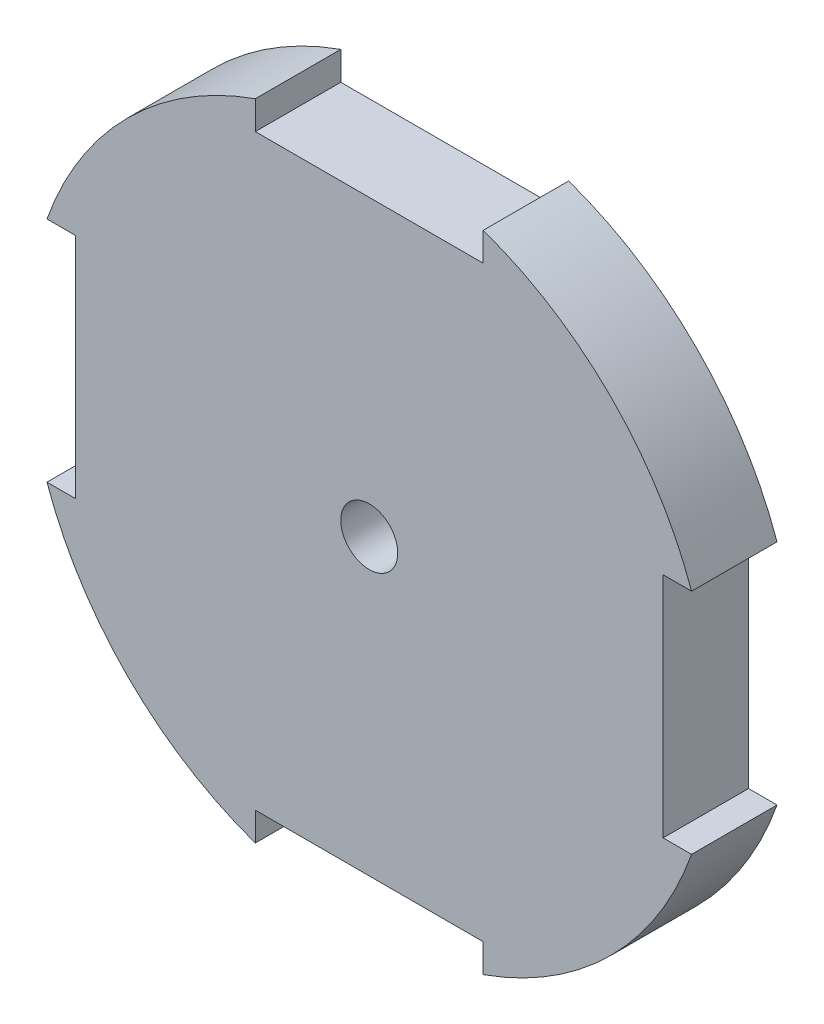
SolidWorks part; units mm, degrees
material "6061 Alloy"
ref_plane "Front Plane" through (0, 0, 0) normal (0, 0, 1) x (1, 0, 0)
ref_plane "Top Plane" through (0, 0, 0) normal (0, 1, 0) x (1, 0, 0)
ref_plane "Right Plane" through (0, 0, 0) normal (1, 0, 0) x (0, 0, -1)
sketch "Sketch1" plane through (0, 0, 0) normal (0, 0, 1) x (1, 0, 0)
  line L0 (-25.4, 71.842) -> (-25.4, 65.492)
  line L1 (-25.4, 65.492) -> (25.4, 65.492)
  line L2 (25.4, 65.492) -> (25.4, 71.842)
  line L3 (65.492, 25.4) -> (65.492, -25.4)
  line L4 (71.842, 25.4) -> (65.492, 25.4)
  line L5 (65.492, -25.4) -> (71.842, -25.4)
  line L6 (25.4, -65.492) -> (-25.4, -65.492)
  line L7 (25.4, -71.842) -> (25.4, -65.492)
  line L8 (-25.4, -65.492) -> (-25.4, -71.842)
  line L9 (-65.492, -25.4) -> (-65.492, 25.4)
  line L10 (-71.842, -25.4) -> (-65.492, -25.4)
  line L11 (-65.492, 25.4) -> (-71.842, 25.4)
  arc A0 (-25.4, 71.842) -> (-71.842, 25.4) centre (0, 0) ccw
  arc A1 (71.842, 25.4) -> (25.4, 71.842) centre (0, 0) ccw
  arc A2 (25.4, -71.842) -> (71.842, -25.4) centre (0, 0) ccw
  arc A3 (-71.842, -25.4) -> (-25.4, -71.842) centre (0, 0) ccw
  point P8 (0, 65.492)
  dimension "D1" = 50.8
  dimension "D2" = 152.4
  dimension "D3" = 6.35
  dimension "D4" = 4
extrude "Boss-Extrude2" add sketch "Sketch1" along normal mid plane 19.05 contours L1 L2 A1 L4 L3 L5 A2 L7 L6 L8 A3 L10 L9 L11 A0 L0
sketch "Sketch3" plane through (0, 0, 9.525) normal (0, 0, 1) x (1, 0, 0)
  circle A0 centre (0, 0) radius 6.35
  dimension "D1" = 12.7
extrude "Cut-Extrude2" cut sketch "Sketch3" against normal blind 19.05
